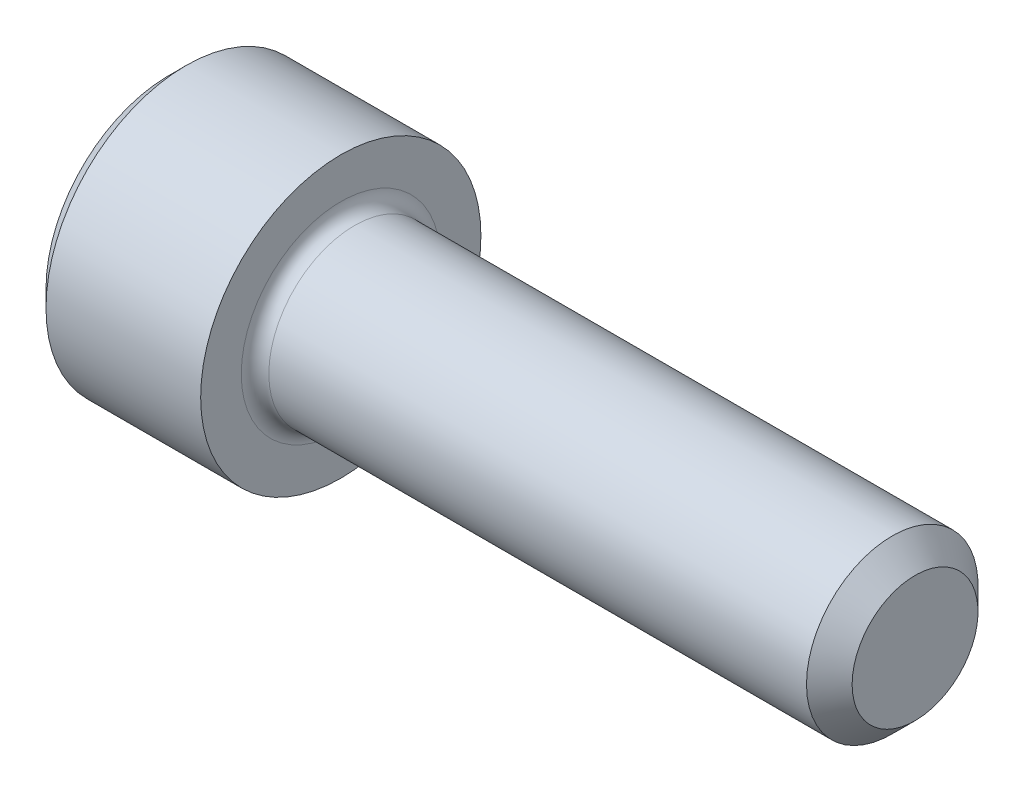
SolidWorks part; units mm, degrees
material "Alloy Steel"
ref_plane "Plane1" through (0, 0, 0) normal (0, 0, 1) x (1, 0, 0)
ref_plane "Plane2" through (0, 0, 0) normal (0, 1, 0) x (1, 0, 0)
ref_plane "Plane3" through (0, 0, 0) normal (1, 0, 0) x (0, 0, -1)
sketch "BodySke" plane through (0, 0, 0) normal (0, 0, 1) x (1, 0, 0)
  line L0 (0, 0) -> (0, 2.0447)
  line L1 (0.2794, 2.3241) -> (2.8448, 2.3241)
  line L2 (2.8448, 2.3241) -> (2.8448, 1.4224)
  line L3 (2.8448, 1.4224) -> (11.9913, 1.4224)
  line L4 (12.3698, 1.0439) -> (12.3698, 0)
  line L5 (12.3698, 0) -> (0, 0)
  line L6 (-31.75, 0) -> (127, 0) construction
  line L7 (0, 2.0447) -> (0.2794, 2.3241)
  line L8 (12.3698, 1.0439) -> (11.9913, 1.4224)
  line L9 (0, -2.0447) -> (0.2794, -2.3241) construction
  line L10 (12.3698, -1.0439) -> (11.9913, -1.4224) construction
  line L11 (3.4798, 9.525) -> (3.4798, 3.175) construction
  line L12 (2.8448, 9.525) -> (2.8448, 3.175) construction
  line L13 (-25.7302, 9.525) -> (-25.7302, 3.175) construction
  dimension "Diameter" = 2.8448
  dimension "Head_ht" = 2.8448
  dimension "Length" = 9.525
  dimension "Body_ch_ang" = 45
  dimension "Head_dia" = 4.6482
  dimension "Head_ch_ang" = 45
  dimension "Head_side_ht" = 2.5654
  dimension "Minor_dia" = 2.0879
  dimension "Advance" = 0.635
  dimension "Thread_nom" = 9.525
  dimension "Thread_length" = 38.1
revolve "Base-Revolve" add sketch "BodySke"
cosmetic thread "ThreadCosmetic"
fillet "Fillet1" radius 0.2286 1 edges at (2.8448, 0, 1.4224)
sketch "Sketch2" plane through (0, 0, 0) normal (0, 0, 1) x (1, 0, 0)
  line L0 (0, 1.1938) -> (1.2954, 1.1938)
  line L1 (1.2954, 1.1938) -> (1.9846, 0)
  line L2 (-31.75, 0) -> (127, 0) construction
  line L3 (1.9846, 0) -> (0, 0)
  line L4 (0, 0) -> (0, 1.1938)
  line L5 (0, 2.0447) -> (0, -2.0447) construction
  line L6 (0, 0) -> (47.625, 0) construction
  line L7 (2.8448, -2.3241) -> (2.8448, 2.3241) construction
  dimension "D1" = 1.1938
  dimension "D2" = 60
  dimension "Wall_thickness" = 1.5494
revolve "Hex-PreBroach" cut sketch "Sketch2" angle 360 about L6
sketch "Sketch3" plane through (0, 0, 0) normal (-1, 0, 0) x (0, 0.5, 0.866)
  line L0 (0.6892, 1.1938) -> (-0.6892, 1.1938)
  line L1 (-0.6892, 1.1938) -> (-1.3785, 0)
  line L2 (0.6892, 1.1938) -> (1.3785, 0)
  line L3 (0.6892, -1.1938) -> (1.3785, 0)
  line L4 (0.6892, -1.1938) -> (-0.6892, -1.1938)
  line L5 (-0.6892, -1.1938) -> (-1.3785, 0)
  dimension "D1" = 1.1938
  dimension "D2" = 1.1938
  dimension "Hex_size" = 2.3876
extrude "Hex" cut sketch "Sketch3" against normal blind 1.2954
equation "\"D2@Sketch3\" = \"Hex_size@Sketch3\" / 2"
equation "\"D1@Sketch3\" = \"Hex_size@Sketch3\" / 2"
equation "\"D1@Sketch2\" = \"Hex_size@Sketch3\" / 2"
equation "\"Thread_minor@ThreadCosmetic\"  =  \"Minor_dia@BodySke\""
equation "\"Wall_thickness@Sketch2\" = \"Head_ht@BodySke\" - \"Key_eng@Hex\""
equation "\"Thread_length@ThreadCosmetic\" = ((sgn( (\"Length@BodySke\" - \"Advance@BodySke\" ) - \"Thread_nom@BodySke\" )-1)*( (\"Length@BodySke\" - \"Advance@BodySke\" ) - \"Thread_nom@BodySke\" ))/-2+ \"Thread_nom@BodySke\""
